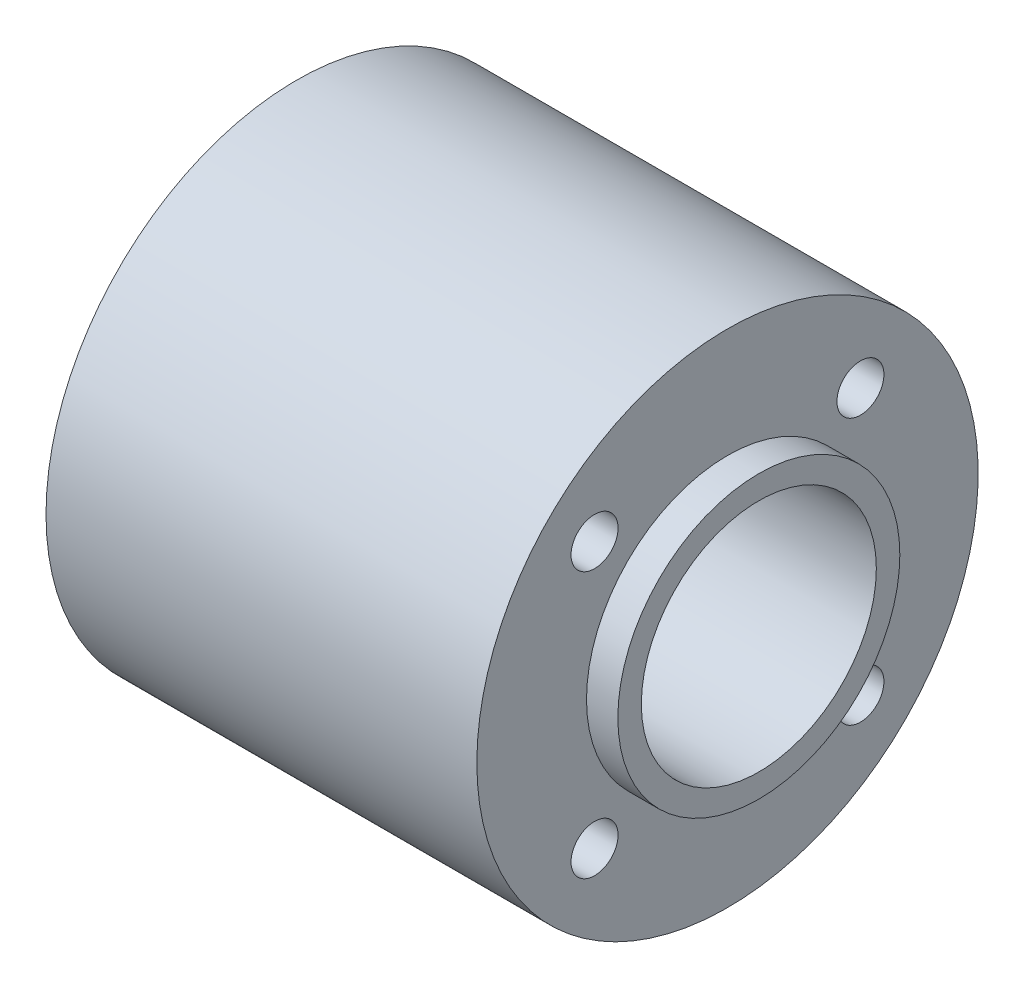
SolidWorks part; units mm, degrees
ref_plane "Front Plane" through (0, 0, 0) normal (0, 0, 1) x (1, 0, 0)
ref_plane "Top Plane" through (0, 0, 0) normal (0, 1, 0) x (1, 0, 0)
ref_plane "Right Plane" through (0, 0, 0) normal (1, 0, 0) x (0, 0, -1)
sketch "Sketch1" plane through (0, 0, 0) normal (0, 0, 1) x (1, 0, 0)
  line L0 (0, 0) -> (0, 7609.8744) construction
  line L1 (0, 0) -> (7609.8744, 0) construction
  line L2 (0, 9) -> (2, 9)
  line L3 (2, 9) -> (2, 16)
  line L4 (2, 16) -> (29.5, 16)
  line L5 (29.5, 16) -> (29.5, 9)
  line L6 (29.5, 9) -> (31.5, 9)
  line L7 (31.5, 9) -> (31.5, 7.5)
  line L8 (31.5, 7.5) -> (0, 7.5)
  line L9 (0, 7.5) -> (0, 9)
  dimension "D1" = 18
  dimension "D2" = 15
  dimension "D3" = 27.5
  dimension "D4" = 2
  dimension "D5" = 2
  dimension "D6" = 32
revolve "Revolve1" add sketch "Sketch1" angle 360 about L1
sketch "Sketch2" plane through (2, 0, 0) normal (-1, 0, 0) x (0, 0, 1)
  line L0 (0, 0) -> (0, 12) construction
  line L1 (0, 0) -> (-8.4853, 8.4853) construction
  circle A0 centre (0, 0) radius 12 construction
  circle A1 centre (-8.4853, 8.4853) radius 1.5
  circle A2 centre (8.4853, 8.4853) radius 1.5
  circle A3 centre (8.4853, -8.4853) radius 1.5
  circle A4 centre (-8.4853, -8.4853) radius 1.5
  dimension "D1" = 24
  dimension "D3" = 3
  dimension "D2" = 45
  dimension "D4" = 4
extrude "Cut-Extrude1" cut sketch "Sketch2" against normal through all
ref_plane "Plane1" through (15.75, 0, 0) normal (-1, 0, 0) x (0, 0, 1)
